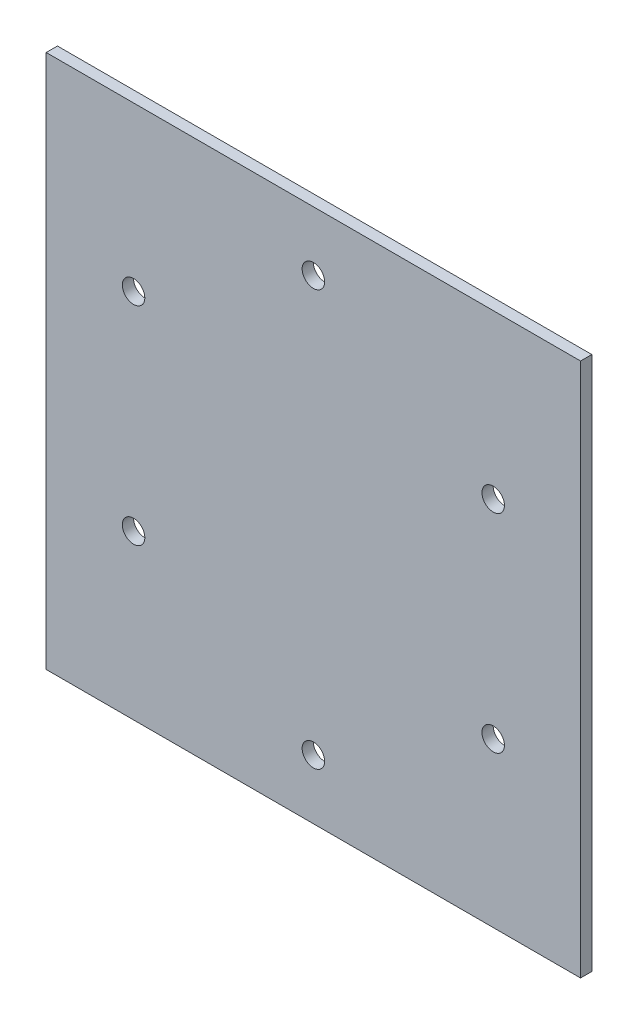
SolidWorks part; units mm, degrees
ref_plane "Alzado" through (0, 0, 0) normal (0, 0, 1) x (1, 0, 0)
ref_plane "Planta" through (0, 0, 0) normal (0, 1, 0) x (1, 0, 0)
ref_plane "Vista lateral" through (0, 0, 0) normal (1, 0, 0) x (0, 0, -1)
sketch "Croquis1" plane through (0, 0, 0) normal (0, 0, 1) x (1, 0, 0)
  line L1 (0, 0) -> (190, 0)
  line L2 (0, 0) -> (0, 190)
  line L3 (0, 190) -> (190, 190)
  line L4 (190, 0) -> (190, 190)
  dimension "D1" = 190
  dimension "D2" = 190
extrude "Saliente-Extruir1" add sketch "Croquis1" along normal mid plane 4
sketch "Croquis2" plane through (0, 0, 2) normal (0, 0, 1) x (1, 0, 0)
  line L0 (190, 190) -> (0, 190) construction
  circle A0 centre (95, 168.86) radius 4
  circle A1 centre (158.9387, 131.945) radius 4
  circle A2 centre (158.9387, 58.115) radius 4
  circle A3 centre (95, 21.2) radius 4
  circle A4 centre (31.0613, 58.115) radius 4
  circle A5 centre (31.0613, 131.945) radius 4
  point P17 (95, 95.03)
  dimension "D1" = 8
  dimension "D2" = 21.14
  dimension "D3" = 6
extrude "Cortar-Extruir2" cut sketch "Croquis2" against normal blind 4
